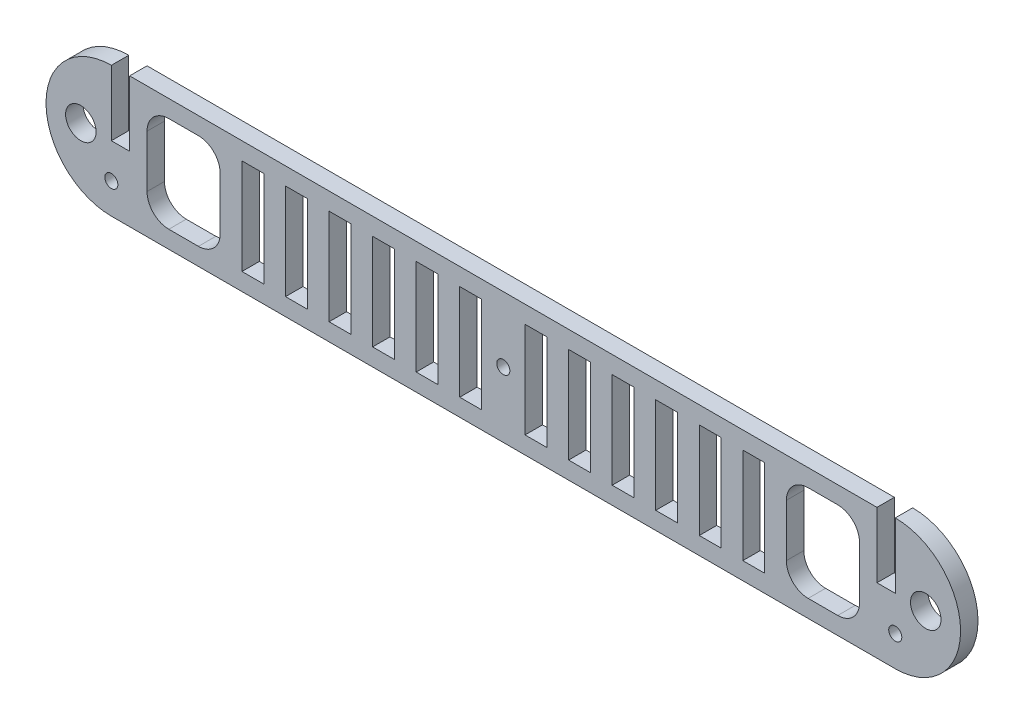
SolidWorks part; units mm, degrees
ref_plane "Front" through (0, 0, 0) normal (0, 0, 1) x (1, 0, 0)
ref_plane "Top" through (0, 0, 0) normal (0, 1, 0) x (1, 0, 0)
ref_plane "Right" through (0, 0, 0) normal (1, 0, 0) x (0, 0, -1)
sketch "Эскиз1" plane through (0, 0, 0) normal (0, 0, 1) x (1, 0, 0)
  line L0 (-90, 15) -> (90, 15)
  line L1 (-90, -15) -> (90, -15)
  line L2 (0, 15) -> (0, -15) construction
  line L3 (-75, 10.9808) -> (0, 10.9808)
  line L4 (-75, 10.9808) -> (-90, -15)
  line L5 (-75, 10.9808) -> (-75, -3.1953) construction
  line L6 (75, 10.9808) -> (90, -15) construction
  line L7 (1.3332, 10.9808) -> (0, 10.9808)
  line L8 (0, 10.9808) -> (0, -15)
  arc A0 (90, -15) -> (90, 15) centre (90, 0) ccw
  arc A1 (-90, -15) -> (-90, 15) centre (-90, 0) cw
  dimension "D1" = 150
  dimension "D2" = 180
  dimension "D3" = 30
  dimension "D4" = 30
extrude "Бобышка-Вытянуть1" add sketch "Эскиз1" along normal mid plane 4 contours A1 L4 L3 L6 A0 L0 | L6 L3 L4 L1
sketch "Эскиз11" plane through (0, 0, -2) normal (0, 0, -1) x (-1, 0, 0)
  line L0 (90, 15) -> (-90, 15) construction
  line L1 (-90, 15) -> (-85.8, 15)
  line L2 (-90, 15) -> (-90, 0)
  line L3 (-90, 0) -> (-85.8, 0)
  line L4 (-85.8, 15) -> (-85.8, 0)
  line L5 (90, 15) -> (85.8, 15)
  line L6 (90, 15) -> (90, 0)
  line L7 (90, 0) -> (85.8, 0)
  line L8 (85.8, 15) -> (85.8, 0)
  line L9 (-81.8, 11) -> (81.8, 11)
  line L10 (-81.8, 11) -> (-81.8, -11)
  line L11 (-81.8, -11) -> (81.8, -11)
  line L12 (81.8, 11) -> (81.8, -11)
  line L13 (90, -15) -> (-90, -15) construction
  line L14 (-55, 11) -> (-55, -11)
  line L15 (-65, 11) -> (-60, 11)
  line L16 (-65, 11) -> (-65, -11)
  line L17 (-65, -11) -> (-60, -11)
  line L18 (-60, 11) -> (-60, -11)
  line L23 (-55, 11) -> (-50, 11)
  line L24 (-50, 11) -> (-50, -11)
  line L25 (-55, -11) -> (-50, -11)
  line L26 (-45, 11) -> (-45, -11)
  line L27 (-45, 11) -> (-40, 11)
  line L28 (-40, 11) -> (-40, -11)
  line L29 (-45, -11) -> (-40, -11)
  line L30 (-35, 11) -> (-35, -11)
  line L31 (-35, 11) -> (-30, 11)
  line L32 (-30, 11) -> (-30, -11)
  line L33 (-35, -11) -> (-30, -11)
  line L34 (-25, 11) -> (-25, -11)
  line L35 (-25, 11) -> (-20, 11)
  line L36 (-20, 11) -> (-20, -11)
  line L37 (-25, -11) -> (-20, -11)
  line L38 (-15, 11) -> (-15, -11)
  line L39 (-15, 11) -> (-10, 11)
  line L40 (-10, 11) -> (-10, -11)
  line L41 (-15, -11) -> (-10, -11)
  line L42 (-5, 11) -> (-5, -11)
  line L43 (-5, 11) -> (0, 11)
  line L44 (0, 11) -> (0, -11)
  line L45 (-5, -11) -> (0, -11)
  line L46 (15, 11) -> (10, 11)
  line L47 (10, 11) -> (10, -11)
  line L48 (15, -11) -> (10, -11)
  line L49 (15, 11) -> (15, -11)
  line L50 (25, 11) -> (20, 11)
  line L51 (20, 11) -> (20, -11)
  line L52 (25, -11) -> (20, -11)
  line L53 (25, 11) -> (25, -11)
  line L54 (35, 11) -> (30, 11)
  line L55 (30, 11) -> (30, -11)
  line L56 (35, -11) -> (30, -11)
  line L57 (35, 11) -> (35, -11)
  line L58 (45, 11) -> (40, 11)
  line L59 (40, 11) -> (40, -11)
  line L60 (45, -11) -> (40, -11)
  line L61 (45, 11) -> (45, -11)
  line L62 (55, 11) -> (50, 11)
  line L63 (50, 11) -> (50, -11)
  line L64 (55, -11) -> (50, -11)
  line L65 (55, 11) -> (55, -11)
  line L66 (5, 11) -> (5, -11)
  line L67 (65, -11) -> (60, -11)
  line L68 (60, 11) -> (60, -11)
  line L69 (65, 11) -> (60, 11)
  line L70 (65, 11) -> (65, -11)
  circle A0 centre (-97, 0) radius 3.5
  circle A1 centre (97, 0) radius 3.5
  circle A2 centre (0, 0) radius 1.5
  circle A3 centre (-90, -8) radius 1.5
  circle A4 centre (90, -8) radius 1.5
  line M45 (90, 15) -> (-90, 15)
  dimension "D3" = 7
  dimension "D13" = 3
  dimension "D16" = 3
  dimension "D1" = 4.2
  dimension "D2" = 4.2
  dimension "D4" = 7
  dimension "D5" = 7
  dimension "D6" = 4
  dimension "D7" = 4
  dimension "D8" = 4
  dimension "D9" = 4
  dimension "D10" = 5
  dimension "D11" = 60
  dimension "D14" = 5
  dimension "D15" = 8
  dimension "D12" = 7
extrude "Вырез-Вытянуть1" cut sketch "Эскиз11" against normal blind 10 contours L4 L2 L3 M45 | L16 L9 L10 L11 | L9 L18 L11 L14 | L26 L9 L24 L11 | L30 L9 L28 L11 | L34 L9 L32 L11 | L38 L9 L36 L11 | L42 L9 L40 L11 | L9 L66 L11 L47 | L51 L9 L49 L11 | L55 L9 L53 L11 | L59 L9 L57 L11 | L63 L9 L61 L11 | L68 L9 L65 L11 | L9 L70 L11 L12 | L8 L7 L6 M45 | A1 | A0 | A2 | A3 | A4
fillet "Скругление1" radius 5 8 edges at (65, 11, 0) (81.8, 11, 0) (81.8, -11, 0) (65, -11, 0) (-81.8, -11, 0) (-81.8, 11, 0) (-65, 11, 0) (-65, -11, 0)
